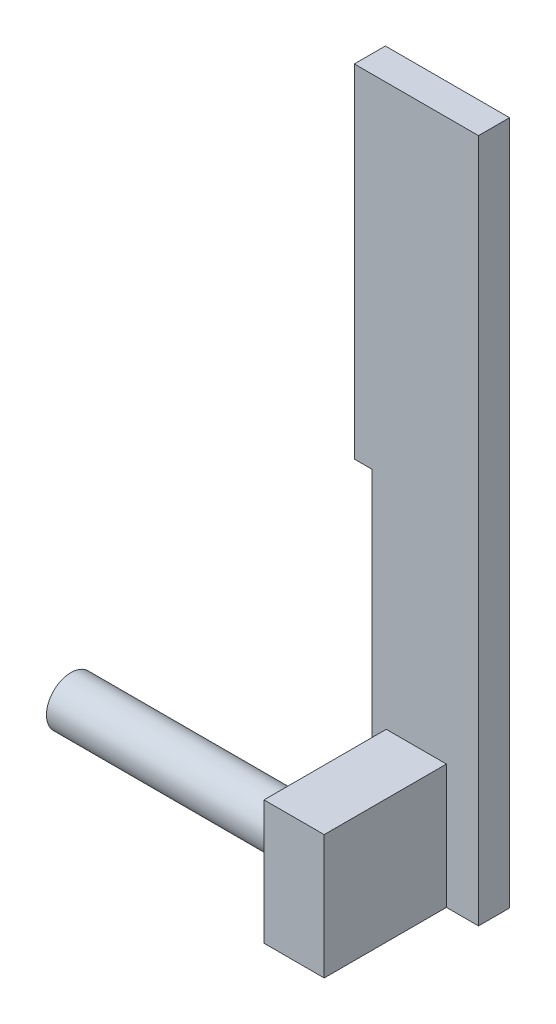
SolidWorks part; units mm, degrees
ref_plane "Alzado" through (0, 0, 0) normal (0, 0, 1) x (1, 0, 0)
ref_plane "Planta" through (0, 0, 0) normal (0, 1, 0) x (1, 0, 0)
ref_plane "Vista lateral" through (0, 0, 0) normal (1, 0, 0) x (0, 0, -1)
sketch "Croquis1" plane through (0, 0, 0) normal (0, 0, 1) x (1, 0, 0)
  line L1 (25.4, -140) -> (-25.4, -140)
  line L2 (25.4, -140) -> (25.4, 140)
  line L3 (25.4, 140) -> (-25.4, 140)
  line L4 (-25.4, -140) -> (-25.4, 140)
  line L5 (25.4, -140) -> (-25.4, 140) construction
  line L6 (25.4, 140) -> (-25.4, -140) construction
  point P0 (0, 0)
  dimension "D1" = 50.8
  dimension "D2" = 280
extrude "Saliente-Extruir1" add sketch "Croquis1" along normal blind 12.7
sketch "Croquis2" plane through (0, 0, 12.7) normal (0, 0, 1) x (1, 0, 0)
  line L0 (-25.4, -140) -> (25.4, -140) construction
  line L1 (-12.3368, -140) -> (12.2736, -140)
  line L2 (-12.3368, -140) -> (-12.3368, -89.2)
  line L3 (-12.3368, -89.2) -> (12.2736, -89.2)
  line L4 (12.2736, -140) -> (12.2736, -89.2)
  dimension "D1" = 50.8
extrude "Saliente-Extruir2" add sketch "Croquis2" along normal blind 50
sketch "Croquis4" plane through (-12.3368, 0, 0) normal (-1, 0, 0) x (0, 0, 1)
  line L0 (62.7, -114.6) -> (12.7, -114.6) construction
  line L1 (62.7, -89.2) -> (62.7, -140) construction
  line L2 (12.7, -89.2) -> (12.7, -140) construction
  line L3 (12.7, 140) -> (12.7, -140) construction
  circle A0 centre (41.7, -114.6) radius 10.0119
  point P8 (0, 0)
  dimension "D1" = 29
extrude "Saliente-Extruir3" add sketch "Croquis4" along normal blind 100
sketch "Croquis5" plane through (0, 0, 12.7) normal (0, 0, 1) x (1, 0, 0)
  line L1 (-25.4, -140) -> (-18.0891, -140)
  line L2 (-25.4, -140) -> (-25.4, 0)
  line L3 (-25.4, 0) -> (-18.0891, 0)
  line L4 (-18.0891, -140) -> (-18.0891, 0)
extrude "Cortar-Extruir1" cut sketch "Croquis5" against normal through all
